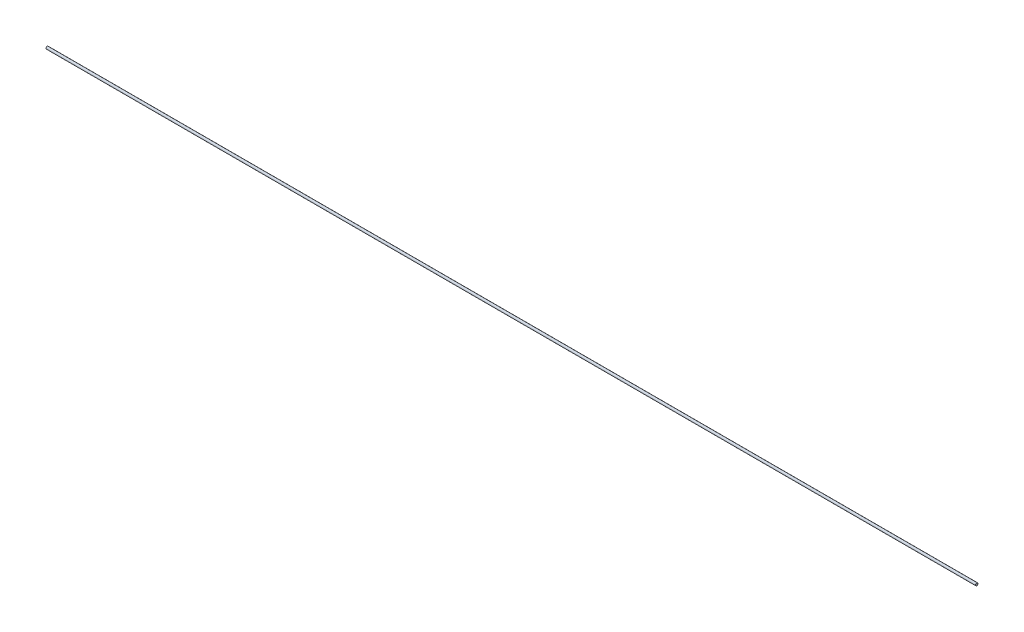
SolidWorks part; units mm, degrees
ref_plane "Спереди" through (0, 0, 0) normal (0, 0, 1) x (1, 0, 0)
ref_plane "Сверху" through (0, 0, 0) normal (0, 1, 0) x (1, 0, 0)
ref_plane "Справа" through (0, 0, 0) normal (1, 0, 0) x (0, 0, -1)
sketch "Эскиз1" plane through (0, 0, 0) normal (1, 0, 0) x (0, 0, -1)
  circle A0 centre (0, 0) radius 2.5
  dimension "D1" = 5
extrude "Бобышка-Вытянуть1" add sketch "Эскиз1" along normal blind 1900
